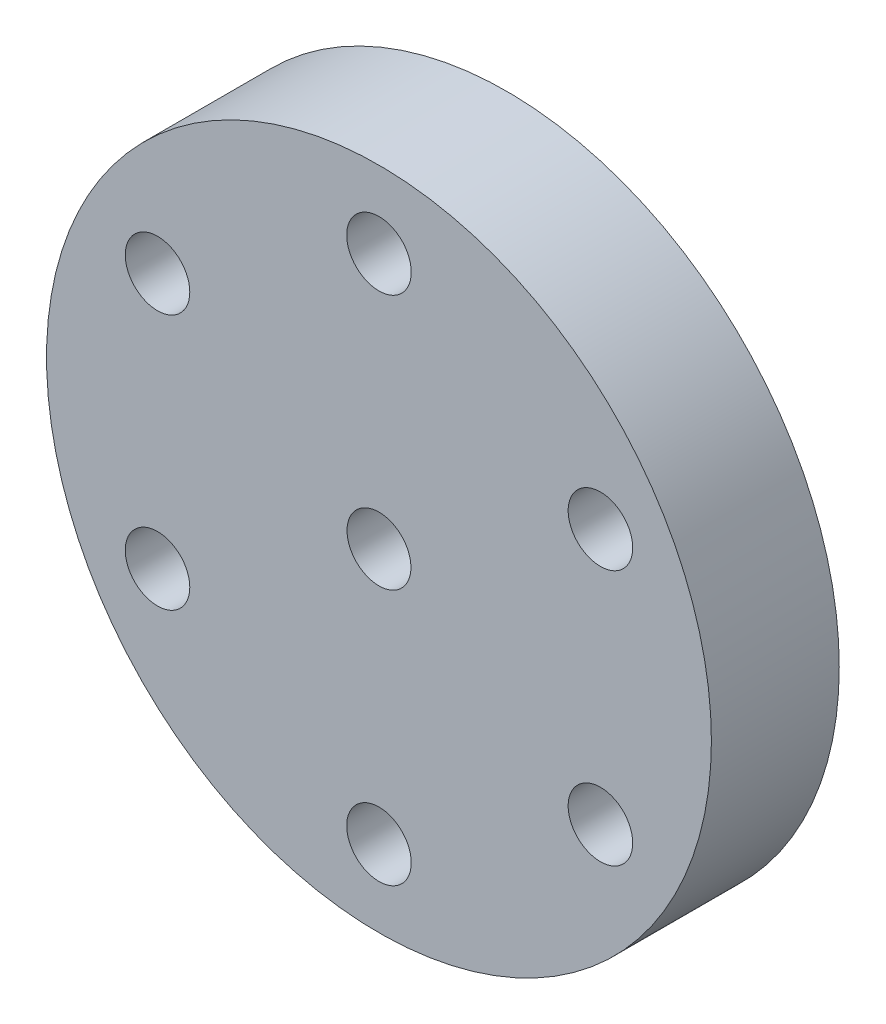
SolidWorks part; units mm, degrees
ref_plane "Front Plane" through (0, 0, 0) normal (0, 0, 1) x (1, 0, 0)
ref_plane "Top Plane" through (0, 0, 0) normal (0, 1, 0) x (1, 0, 0)
ref_plane "Right Plane" through (0, 0, 0) normal (1, 0, 0) x (0, 0, -1)
sketch "Sketch3" plane through (0, 0, 0) normal (0, 0, 1) x (1, 0, 0)
  circle A0 centre (0, 0) radius 26
  circle A1 centre (0, 0) radius 2.5
  circle A2 centre (0, 20) radius 2.5236
  circle A3 centre (17.3205, 10) radius 2.5236
  circle A4 centre (17.3205, -10) radius 2.5236
  circle A5 centre (0, -20) radius 2.5236
  circle A17 centre (-17.3205, -10) radius 2.5236
  circle A18 centre (-17.3205, 10) radius 2.5236
  point P37 (0, 0)
  dimension "D1" = 52
  dimension "D2" = 5
  dimension "D3" = 5.0472
  dimension "D4" = 20
  dimension "D5" = 6
extrude "Boss-Extrude2" add sketch "Sketch3" along normal blind 10
